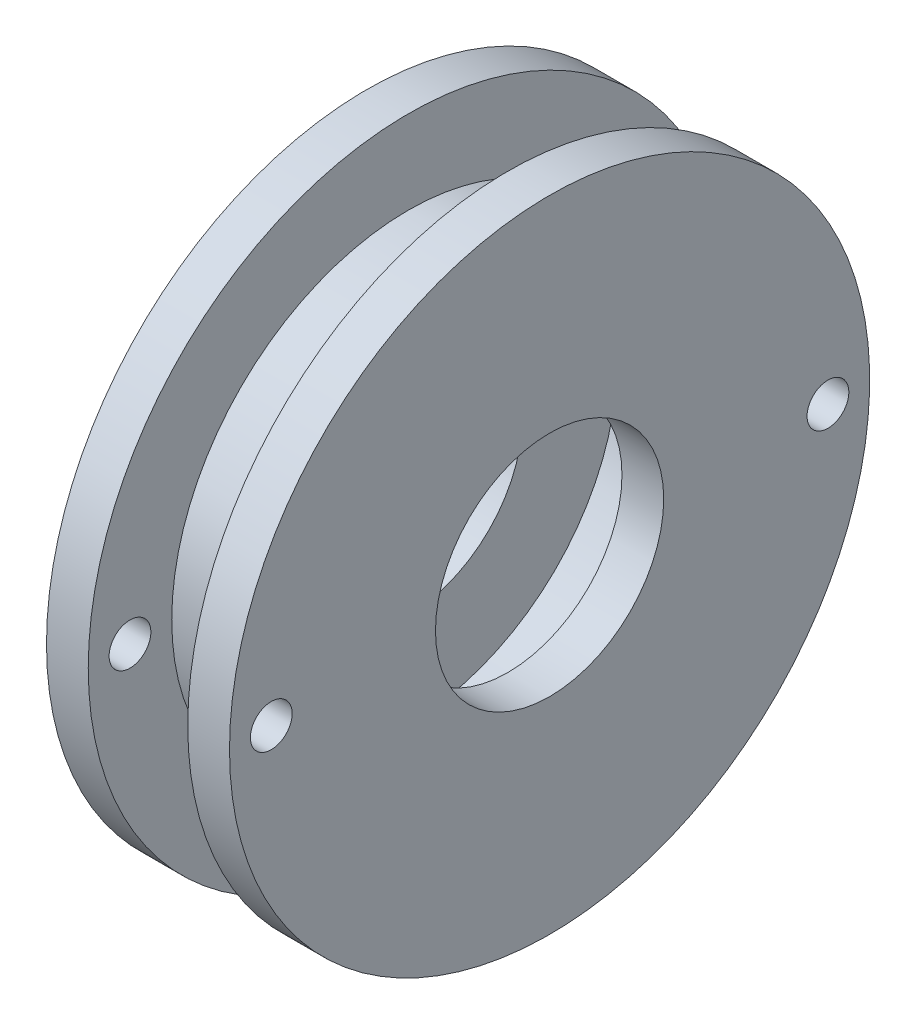
SolidWorks part; units mm, degrees
ref_plane "Front" through (0, 0, 0) normal (0, 0, 1) x (1, 0, 0)
ref_plane "Top" through (0, 0, 0) normal (0, 1, 0) x (1, 0, 0)
ref_plane "Right" through (0, 0, 0) normal (1, 0, 0) x (0, 0, -1)
sketch "草图1" plane through (0, 0, 0) normal (0, 0, 1) x (1, 0, 0)
  line L0 (0, 0) -> (0, 15) construction
  line L1 (-3.575, 15) -> (3.575, 15)
  line L2 (3.575, 15) -> (3.575, 8.2)
  line L3 (3.575, 8.2) -> (6.575, 8.2)
  line L4 (6.575, 8.2) -> (6.575, 23)
  line L5 (6.575, 23) -> (3.575, 23)
  line L6 (3.575, 23) -> (3.575, 17)
  line L7 (3.575, 17) -> (-3.575, 17)
  line L9 (-3.575, 8.2) -> (-6.575, 8.2)
  line L10 (-3.575, 15) -> (-3.575, 8.2)
  line L11 (-6.575, 8.2) -> (-6.575, 23)
  line L12 (-6.575, 23) -> (-3.575, 23)
  line L13 (-3.575, 23) -> (-3.575, 17)
  line L14 (0, 0) -> (8.7124, 0) construction
  dimension "D1" = 15
revolve "旋转1" add sketch "草图1" angle 360 about L14
sketch "草图2" plane through (-6.575, 0, 0) normal (-1, 0, 0) x (0, 0, 1)
  line L0 (0, 0) -> (20, 0) construction
  line L1 (0, 0) -> (0, 23) construction
  circle A0 centre (20, 0) radius 1.5
  circle A1 centre (0, 0) radius 23 construction
  circle A2 centre (-20, 0) radius 1.5
extrude "切除-拉伸1" cut sketch "草图2" against normal blind 30
